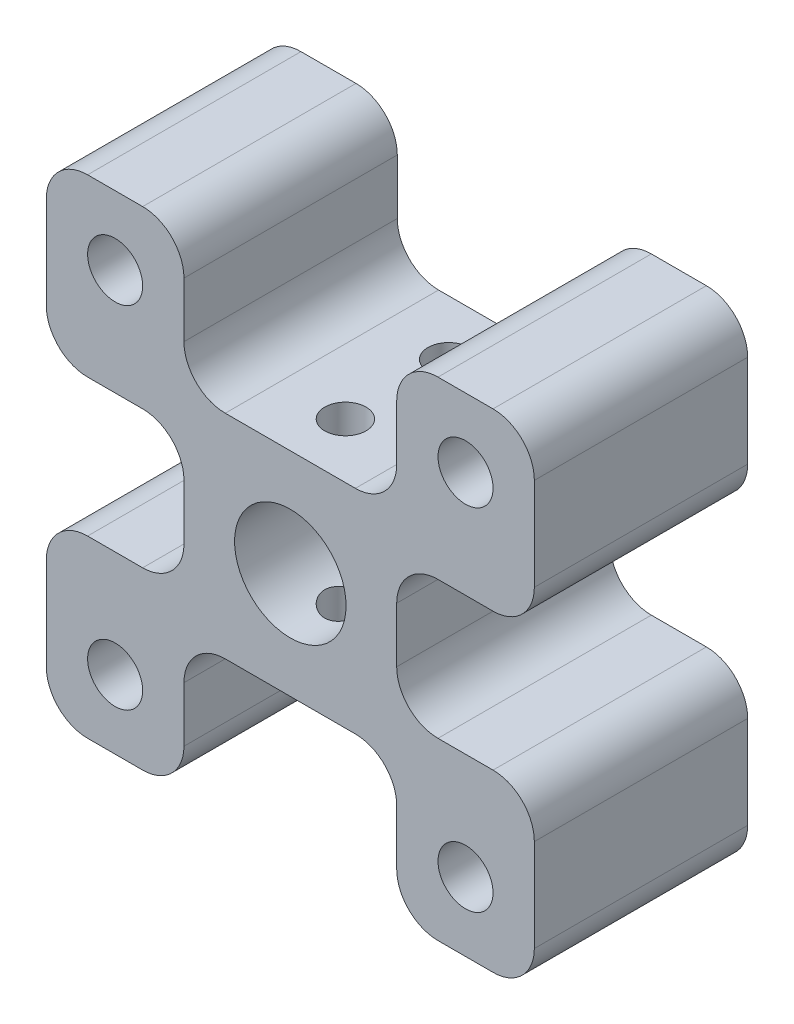
SolidWorks part; units mm, degrees
material "5052-O"
ref_plane "正面" through (0, 0, 0) normal (0, 0, 1) x (1, 0, 0)
ref_plane "平面" through (0, 0, 0) normal (0, 1, 0) x (1, 0, 0)
ref_plane "右側面" through (0, 0, 0) normal (1, 0, 0) x (0, 0, -1)
sketch "ｽｹｯﾁ1" plane through (0, 0, 0) normal (0, 0, 1) x (1, 0, 0)
  line L0 (-7.7279, 17.7279) -> (-7.7279, 7.7279)
  line L1 (17.7279, -17.7279) -> (7.7279, -17.7279)
  line L2 (17.7279, -17.7279) -> (17.7279, -5)
  line L3 (17.7279, 17.7279) -> (7.7279, 17.7279)
  line L4 (-17.7279, -17.7279) -> (-17.7279, -5)
  line L5 (17.7279, -17.7279) -> (-17.7279, 17.7279) construction
  line L6 (17.7279, 17.7279) -> (-17.7279, -17.7279) construction
  line L7 (12.7279, -12.7279) -> (-12.7279, -12.7279) construction
  line L8 (12.7279, -12.7279) -> (12.7279, 12.7279) construction
  line L9 (12.7279, 12.7279) -> (-12.7279, 12.7279) construction
  line L10 (-12.7279, -12.7279) -> (-12.7279, 12.7279) construction
  line L11 (12.7279, -12.7279) -> (-12.7279, 12.7279) construction
  line L12 (12.7279, 12.7279) -> (-12.7279, -12.7279) construction
  line L17 (5, -5) -> (-5, 5) construction
  line L18 (5, 5) -> (-5, -5) construction
  line L19 (-7.7279, 7.7279) -> (7.7279, 7.7279)
  line L20 (7.7279, 7.7279) -> (7.7279, 17.7279)
  line L21 (-7.7279, -17.7279) -> (-7.7279, -7.7279)
  line L22 (-7.7279, -7.7279) -> (7.7279, -7.7279)
  line L23 (7.7279, -7.7279) -> (7.7279, -17.7279)
  line L24 (-7.7279, 17.7279) -> (-17.7279, 17.7279)
  line L25 (-7.7279, -17.7279) -> (-17.7279, -17.7279)
  line L26 (-17.7279, 5) -> (-7.7279, 5)
  line L27 (-7.7279, 5) -> (-7.7279, -5)
  line L28 (-7.7279, -5) -> (-17.7279, -5)
  line L29 (17.7279, 5) -> (7.7279, 5)
  line L30 (7.7279, 5) -> (7.7279, -5)
  line L31 (7.7279, -5) -> (17.7279, -5)
  line L33 (-17.7279, 5) -> (-17.7279, 17.7279)
  line L34 (17.7279, 5) -> (17.7279, 17.7279)
  circle A0 centre (-12.7279, 12.7279) radius 2
  circle A1 centre (12.7279, 12.7279) radius 2
  circle A2 centre (12.7279, -12.7279) radius 2
  circle A3 centre (-12.7279, -12.7279) radius 2
  circle A4 centre (0, 0) radius 4.05
  point P0 (0, 0)
  point P6 (0, 0)
  point P15 (0, 0)
  dimension "D1" = 4
  dimension "D2" = 18
  dimension "D15" = 8.1
  dimension "D3" = 5
  dimension "D4" = 12.7279
  dimension "D5" = 10
  dimension "D6" = 10
  dimension "D7" = 10
  dimension "D8" = 10
  dimension "D9" = 10
  dimension "D10" = 10
  dimension "D11" = 10
  dimension "D12" = 10
  dimension "D13" = 10
  dimension "D14" = 10
extrude "ﾎﾞｽ - 押し出し1" add sketch "ｽｹｯﾁ1" along normal blind 15.5
sketch "ｽｹｯﾁ3" plane through (0, 7.7279, 0) normal (0, 1, 0) x (1, 0, 0)
  line L0 (0, 0) -> (0, -15.5) construction
  line L1 (7.7279, 0) -> (-7.7279, 0) construction
  line L2 (7.7279, -15.5) -> (-7.7279, -15.5) construction
  circle A0 centre (0, -4) radius 1.5
  circle A1 centre (0, -11.5) radius 1.5
  dimension "D1" = 3
  dimension "D2" = 3
  dimension "D3" = 4
  dimension "D4" = 4
fillet "ﾌｨﾚｯﾄ3" radius 3 20 edges at (-7.7279, 5, 7.75) (-17.7279, 5, 7.75) (-7.7279, -5, 7.75) (-17.7279, -5, 7.75) (-17.7279, -17.7279, 7.75) (-7.7279, -17.7279, 7.75) (-7.7279, -7.7279, 7.75) (7.7279, -7.7279, 7.75) (17.7279, -17.7279, 7.75) (7.7279, -17.7279, 7.75) (17.7279, -5, 7.75) (7.7279, 5, 7.75) (7.7279, -5, 7.75) (17.7279, 5, 7.75) (17.7279, 17.7279, 7.75) (7.7279, 17.7279, 7.75) (7.7279, 7.7279, 7.75) (-7.7279, 7.7279, 7.75) (-7.7279, 17.7279, 7.75) (-17.7279, 17.7279, 7.75)
extrude "ｶｯﾄ - 押し出し2" cut sketch "ｽｹｯﾁ3" against normal through all
